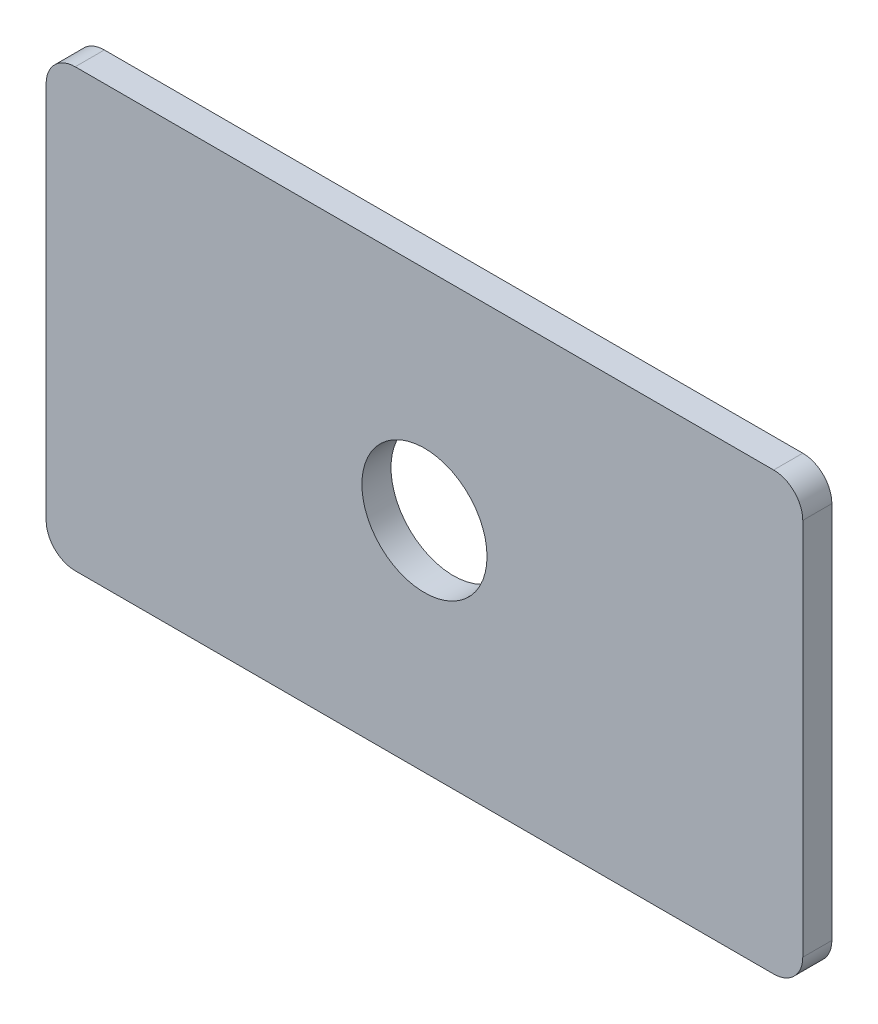
SolidWorks part; units mm, degrees
material "AISI 304"
ref_plane "Спереди" through (0, 0, 0) normal (0, 0, 1) x (1, 0, 0)
ref_plane "Сверху" through (0, 0, 0) normal (0, 1, 0) x (1, 0, 0)
ref_plane "Справа" through (0, 0, 0) normal (1, 0, 0) x (0, 0, -1)
sketch "Эскиз1" plane through (0, 0, 0) normal (0, 0, 1) x (1, 0, 0)
  line L1 (-130, -75) -> (130, -75)
  line L2 (-130, -75) -> (-130, 75)
  line L3 (-130, 75) -> (130, 75)
  line L4 (130, -75) -> (130, 75)
  line L5 (-130, -75) -> (130, 75) construction
  line L6 (-130, 75) -> (130, -75) construction
  circle A0 centre (0, 0) radius 21.5
  point P0 (0, 0)
  dimension "D3" = 43
  dimension "D1" = 260
  dimension "D2" = 150
extrude "Бобышка-Вытянуть1" add sketch "Эскиз1" along normal mid plane 10
fillet "Скругление1" radius 10 4 edges at (-130, -75, 0) (-130, 75, 0) (130, -75, 0) (130, 75, 0)
move or copy body "Тело-Переместить/Копировать2" [suppressed] bodies to move or copy 101 parameters "D1"=0, "D2"=0, "D3"=0
move or copy body "Тело-Переместить/Копировать1" [suppressed] bodies to move or copy 101
